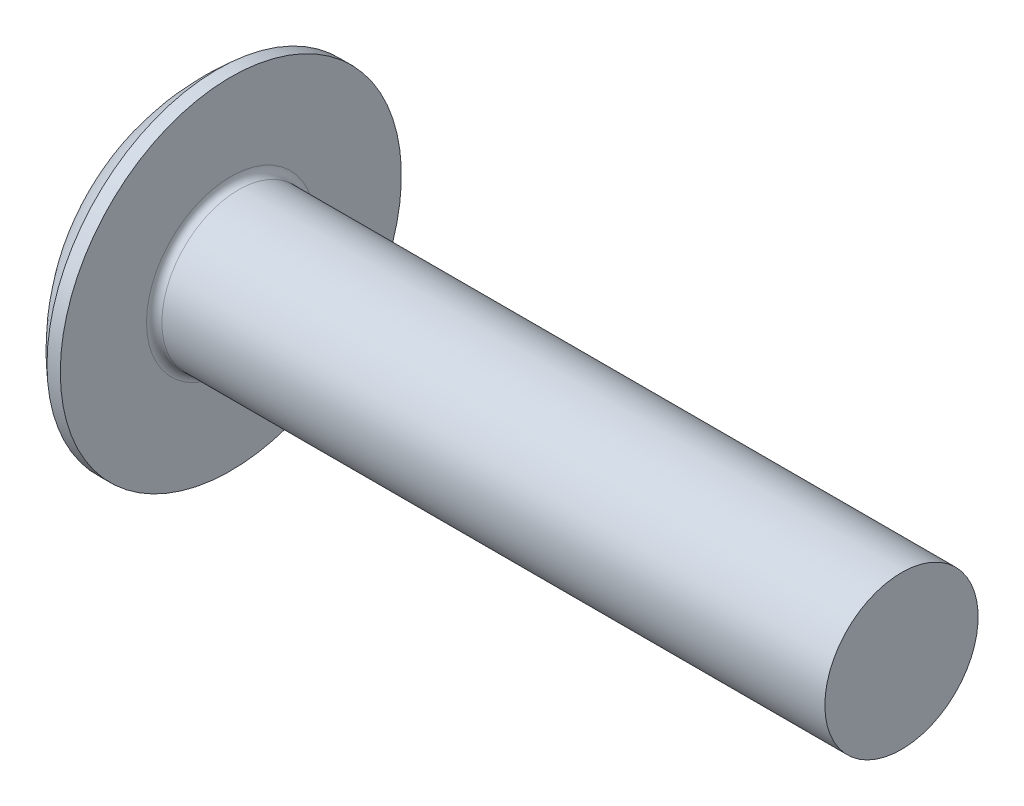
SolidWorks part; units mm, degrees
ref_plane "Plane1" through (0, 0, 0) normal (0, 0, 1) x (1, 0, 0)
ref_plane "Plane2" through (0, 0, 0) normal (0, 1, 0) x (1, 0, 0)
ref_plane "Plane3" through (0, 0, 0) normal (1, 0, 0) x (0, 0, -1)
sketch "BodySke" plane through (0, 0, 0) normal (0, 0, 1) x (1, 0, 0)
  line L0 (4.8, 4) -> (4.8, 8.9)
  line L1 (4.8, 8.9) -> (4.1053, 8.9)
  line L2 (-25.4, 0) -> (127, 0) construction
  line L4 (4.8, 4) -> (39.8, 4)
  line L5 (39.8, 4) -> (39.8, 0)
  line L6 (39.8, 0) -> (0, 0)
  line L7 (4.8, -4) -> (39.8, -4) construction
  line L8 (6.05, 6.35) -> (6.05, -3.175) construction
  line L9 (9.8, 6.35) -> (9.8, -3.175) construction
  arc A0 (0, 0) -> (4.1053, 8.9) centre (11.7, 0) cw
  dimension "Oval_rad" = 11.7
  dimension "Head_ht" = 4.8
  dimension "Diameter" = 8
  dimension "Length" = 35
  dimension "Advance" = 1.25
  dimension "Thread_nom" = 30
  dimension "Head_dia" = 17.8
revolve "Base-Revolve" add sketch "BodySke"
cosmetic thread "ThreadCosmetic" [suppressed]
fillet "Fillet1" radius 0.4 1 edges at (4.8, 0, 4)
sketch "Sketch2" plane through (0, 0, 0) normal (1, 0, 0) x (0, 0, -1)
  line L0 (8.9, -0.8) -> (8.9, 0.8)
  line L1 (8.9, 0.8) -> (-8.9, 0.8)
  line L2 (-8.9, 0.8) -> (-8.9, -0.8)
  line L3 (-8.9, -0.8) -> (8.9, -0.8)
  dimension "D1" = 17.8
  dimension "D2" = 8.9
  dimension "D3" = 0.8
  dimension "Slot_width" = 1.6
extrude "Slot" cut sketch "Sketch2" along normal blind 2.4
sketch "ThdSchSke" plane through (0, 0, 0) normal (0, 0, 1) x (1, 0, 0)
  line L0 (9.8, -3.3095) -> (9.3165, -4)
  line L1 (9.8, -3.3095) -> (10.2835, -4)
  line L2 (10.2835, -4) -> (10.2835, -5)
  line L3 (-3.175, 0) -> (5.1513, 0) construction
  line L5 (10.2835, -5) -> (9.3165, -5)
  line L6 (9.3165, -5) -> (9.3165, -4)
  dimension "Diameter" = 8
  dimension "SideAngle" = 55
  dimension "VeeAngle" = 70
  dimension "Thread_minor" = 6.619
  dimension "Overcut" = 10
  dimension "Start" = 9.8
revolve "ThreadSchematic" [suppressed] cut sketch "ThdSchSke" angle 360 about L3
pattern_linear "ThdSchPat" [suppressed]
equation "' \"Diameter@BodySke\" = 8"
equation "' \"Length@BodySke\" = 35"
equation "' \"Head_dia@BodySke\" = 17.8"
equation "' \"Oval_rad@BodySke\" = 11.7"
equation "' \"Head_ht@BodySke\" = 4.8"
equation "' \"Thread_nom@BodySke\" =  30"
equation "' \"Thread_nom@BodySke\" = 30"
equation "' \"Slot_width@Sketch2\" = 1.6"
equation "' \"Slot_depth@Slot\" = 2.4"
equation "' \"Thread_minor@ThreadCosmetic\" = 6.619"
equation "' \"Advance@BodySke\" = 1.25"
equation "\"D1@Sketch2\" = \"Head_dia@BodySke\""
equation "\"D2@Sketch2\" = \"D1@Sketch2\" / 2"
equation "\"D3@Sketch2\" = \"Slot_width@Sketch2\" / 2"
equation "\"Thread_length@ThreadCosmetic\" = ((sgn( (\"Length@BodySke\" - \"Advance@BodySke\" * 2 ) - \"Thread_nom@BodySke\" )-1)*( (\"Length@BodySke\" - \"Advance@BodySke\" * 2 ) - \"Thread_nom@BodySke\" ))/-2+ \"Thread_nom@BodySke\""
equation "\"Thread_minor@ThdSchSke\" = \"Thread_minor@ThreadCosmetic\""
equation "\"Diameter@ThdSchSke\" = \"Diameter@BodySke\""
equation "\"Overcut@ThdSchSke\" = \"Diameter@BodySke\" * 1.25"
equation "\"Start@ThdSchSke\" = \"Head_ht@BodySke\" + \"Length@BodySke\" - \"Thread_length@ThreadCosmetic\"  '---Non-countersunk---"
equation "\"Num_threads@ThdSchPat\" = int( \"Thread_length@ThreadCosmetic\" / \"Advance@BodySke\" + 0.999 )  + 1"
equation "\"Advance@ThdSchPat\" = \"Thread_length@ThreadCosmetic\" /  (\"Num_threads@ThdSchPat\" - 1) 'relax it"
